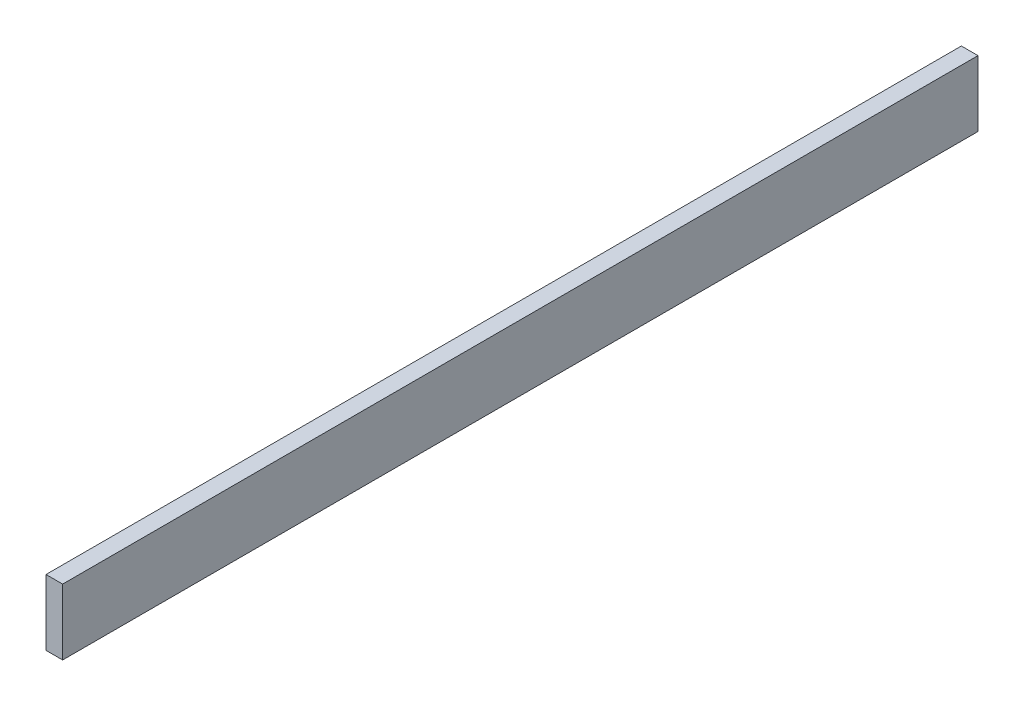
SolidWorks part; units mm, degrees
material "Galvanized Steel"
ref_plane "Front Plane" through (0, 0, 0) normal (0, 0, 1) x (1, 0, 0)
ref_plane "Top Plane" through (0, 0, 0) normal (0, 1, 0) x (1, 0, 0)
ref_plane "Right Plane" through (0, 0, 0) normal (1, 0, 0) x (0, 0, -1)
sketch "Sketch1" plane through (0, 0, 0) normal (0, 0, 1) x (1, 0, 0)
  line L1 (-6.35, -22.606) -> (6.35, -22.606)
  line L2 (-6.35, -22.606) -> (-6.35, 22.606)
  line L3 (-6.35, 22.606) -> (6.35, 22.606)
  line L4 (6.35, -22.606) -> (6.35, 22.606)
  line L5 (-6.35, -22.606) -> (6.35, 22.606) construction
  line L6 (-6.35, 22.606) -> (6.35, -22.606) construction
  point P0 (0, 0)
  dimension "D1" = 45.212
  dimension "D2" = 12.7
extrude "Boss-Extrude1" add sketch "Sketch1" along normal blind 558.8
sketch "Sketch2" plane through (0, 0, 558.8) normal (0, 0, 1) x (1, 0, 0)
  line L0 (-6.35, 22.606) -> (-6.35, -22.606) construction
  line L1 (-6.35, 20.066) -> (3.81, 20.066)
  line L2 (-6.35, 20.066) -> (-6.35, -20.066)
  line L3 (-6.35, -20.066) -> (3.81, -20.066)
  line L4 (3.81, 20.066) -> (3.81, -20.066)
  line L5 (6.35, 22.606) -> (-6.35, 22.606) construction
  line L6 (6.35, -22.606) -> (6.35, 22.606) construction
  line L7 (-6.35, -22.606) -> (6.35, -22.606) construction
  dimension "D1" = 2.54
  dimension "D2" = 2.54
  dimension "D3" = 2.54
extrude "Cut-Extrude1" cut sketch "Sketch2" against normal through all flip side to cut
